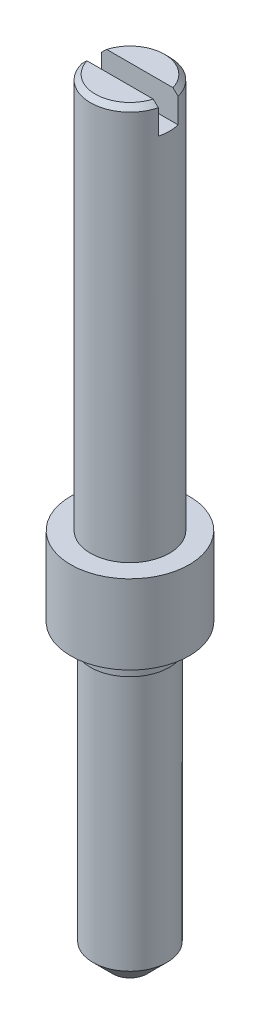
SolidWorks part; units mm, degrees
ref_plane "Face" through (0, 0, 0) normal (0, 0, 1) x (1, 0, 0)
ref_plane "Dessus" through (0, 0, 0) normal (0, 1, 0) x (1, 0, 0)
ref_plane "Droite" through (0, 0, 0) normal (1, 0, 0) x (0, 0, -1)
sketch "Esquisse1" plane through (0, 0, 0) normal (0, 1, 0) x (1, 0, 0)
  circle A0 centre (0, 0) radius 3
  dimension "D1" = 6
extrude "Boss.-Extru.1" add sketch "Esquisse1" along normal blind 4
sketch "Esquisse2" plane through (0, 4, 0) normal (0, 1, 0) x (1, 0, 0)
  circle A0 centre (0, 0) radius 2
  dimension "D1" = 4
extrude "Boss.-Extru.2" add sketch "Esquisse2" along normal blind 20
chamfer "Chanfrein1" distance 0.25 angle 45 1 edges at (0, 24, 2)
sketch "Esquisse3" plane through (0, 24, 0) normal (0, 1, 0) x (1, 0, 0)
  line L0 (0, 0) -> (2, 0) construction
  line L1 (-1.9365, -0.5) -> (1.9365, -0.5)
  line L2 (-1.9365, 0.5) -> (1.9365, 0.5)
  circle A0 centre (0, 0) radius 2 construction
  arc A1 (-1.9365, 0.5) -> (-1.9365, -0.5) centre (0, 0) ccw
  arc A2 (1.9365, -0.5) -> (1.9365, 0.5) centre (0, 0) ccw
  dimension "D1" = 1
extrude "Enlèv. mat.-Extru.1" cut sketch "Esquisse3" against normal blind 1.5
sketch "Esquisse4" plane through (0, 0, 0) normal (0, -1, 0) x (1, 0, 0)
  circle A0 centre (0, 0) radius 2
  dimension "D1" = 4
extrude "Boss.-Extru.3" add sketch "Esquisse4" along normal blind 1
sketch "Esquisse5" plane through (0, -1, 0) normal (0, -1, 0) x (1, 0, 0)
  circle A0 centre (0, 0) radius 1.875
  dimension "D1" = 3.75
extrude "Boss.-Extru.4" add sketch "Esquisse5" along normal blind 14
cosmetic thread "Représentation de filetage1" parameters "D2"=3.2
chamfer "Chanfrein2" distance 1 angle 45 1 edges at (0, -15, -1.875)
